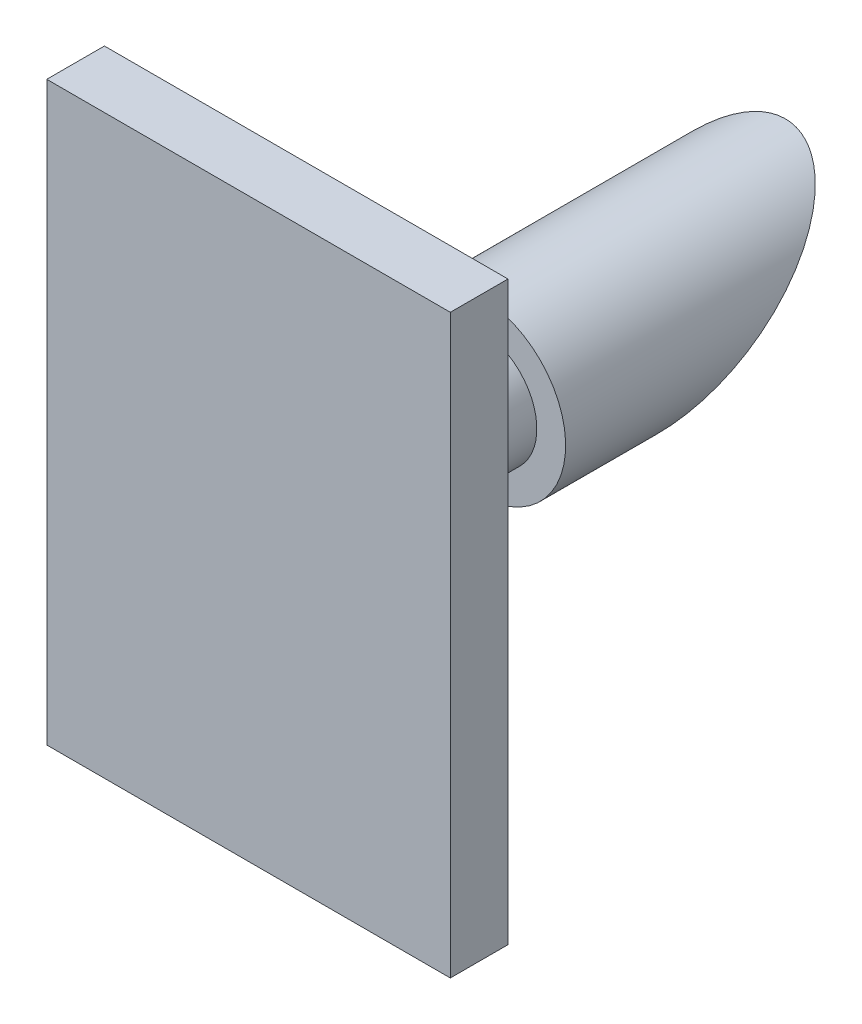
SolidWorks part; units mm, degrees
ref_plane "Płaszczyzna przednia" through (0, 0, 0) normal (0, 0, 1) x (1, 0, 0)
ref_plane "Płaszczyzna górna" through (0, 0, 0) normal (0, 1, 0) x (1, 0, 0)
ref_plane "Płaszczyzna prawa" through (0, 0, 0) normal (1, 0, 0) x (0, 0, -1)
sketch "Szkic1" plane through (0, 0, 0) normal (0, 0, 1) x (1, 0, 0)
  line L1 (-35, -50) -> (35, -50)
  line L2 (-35, -50) -> (-35, 50)
  line L3 (-35, 50) -> (35, 50)
  line L4 (35, -50) -> (35, 50)
  line L5 (-35, -50) -> (35, 50) construction
  line L6 (-35, 50) -> (35, -50) construction
  point P0 (0, 0)
  dimension "D1" = 70
  dimension "D2" = 100
extrude "Dodanie-wyciągnięcie1" add sketch "Szkic1" along normal blind 10
sketch "Szkic2" plane through (0, 0, 0) normal (0, 0, -1) x (-1, 0, 0)
  circle A0 centre (0, 0) radius 10
extrude "Dodanie-wyciągnięcie2" add sketch "Szkic2" along normal blind 30
sketch "Szkic3" plane through (0, 0, -30) normal (0, 0, -1) x (-1, 0, 0)
  circle A0 centre (0, 0) radius 15
extrude "Dodanie-wyciągnięcie3" add sketch "Szkic3" along normal blind 60
sketch "Szkic4" plane through (0, 0, 0) normal (1, 0, 0) x (0, 0, -1)
  line L0 (0, -50) -> (83.1257, 15)
  line L1 (90, 15) -> (30, 15) construction
  line L2 (83.1257, 15) -> (90, 15)
  line L3 (90, 15) -> (90, -15)
  line L4 (90, -15) -> (44.76, -15)
extrude "Wytnij-wyciągnięcie1" cut sketch "Szkic4" against normal mid plane 60 contours L4 L3 L2 L0
